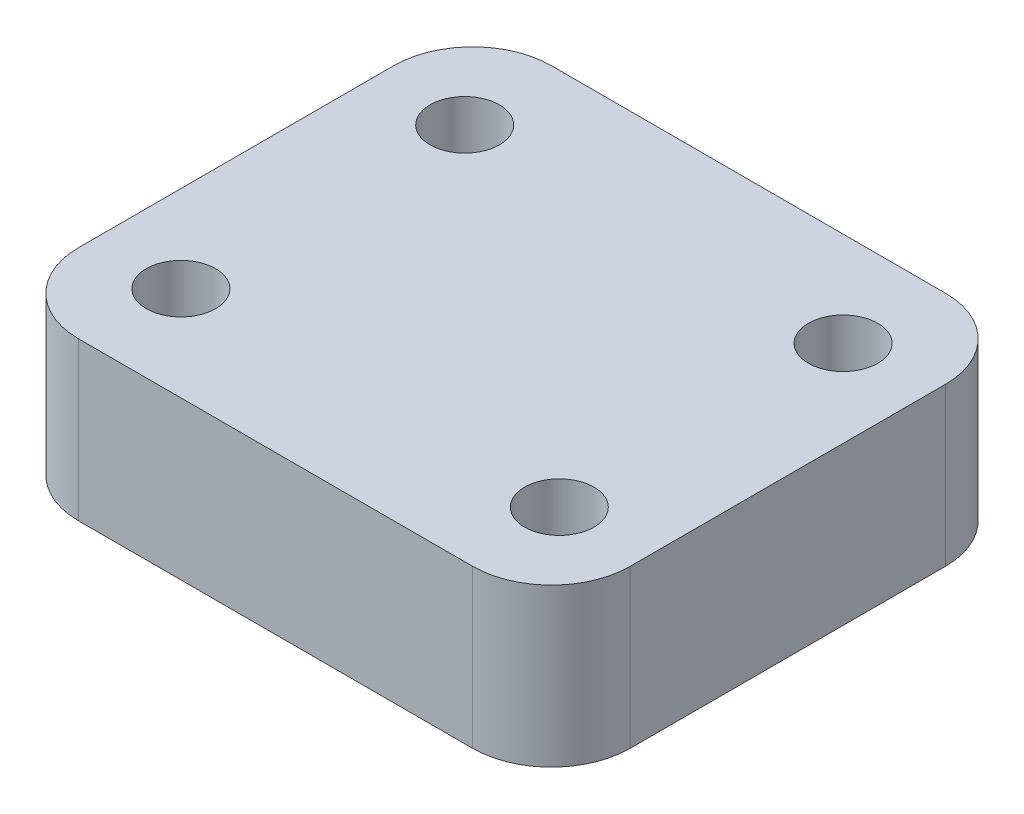
SolidWorks part; units mm, degrees
ref_plane "Front Plane" through (0, 0, 0) normal (0, 0, 1) x (1, 0, 0)
ref_plane "Top Plane" through (0, 0, 0) normal (0, 1, 0) x (1, 0, 0)
ref_plane "Right Plane" through (0, 0, 0) normal (1, 0, 0) x (0, 0, -1)
sketch "Sketch1" plane through (0, 0, 0) normal (0, 1, 0) x (1, 0, 0)
  line L1 (-17.5, 15) -> (17.5, 15)
  line L2 (-17.5, 15) -> (-17.5, -15)
  line L3 (-17.5, -15) -> (17.5, -15)
  line L4 (17.5, 15) -> (17.5, -15)
  line L5 (-17.5, 15) -> (17.5, -15) construction
  line L6 (-17.5, -15) -> (17.5, 15) construction
  point P0 (0, 0)
  dimension "D1" = 35
  dimension "D2" = 30
extrude "Boss-Extrude1" add sketch "Sketch1" along normal blind 10
sketch "Sketch2" plane through (0, 10, 0) normal (0, 1, 0) x (1, 0, 0)
  line L1 (-12, 9) -> (12, 9) construction
  line L2 (-12, 9) -> (-12, -9) construction
  line L3 (-12, -9) -> (12, -9) construction
  line L4 (12, 9) -> (12, -9) construction
  line L5 (-12, 9) -> (12, -9) construction
  line L6 (-12, -9) -> (12, 9) construction
  circle A0 centre (-12, 9) radius 2.2
  circle A1 centre (12, 9) radius 2.2
  circle A2 centre (12, -9) radius 2.2
  circle A3 centre (-12, -9) radius 2.2
  point P0 (0, 0)
  dimension "D3" = 4.4
  dimension "D1" = 24
  dimension "D2" = 18
extrude "Cut-Extrude1" cut sketch "Sketch2" against normal through all
fillet "Fillet1" radius 5 4 edges at (-17.5, 5, -15) (17.5, 5, -15) (17.5, 5, 15) (-17.5, 5, 15)
